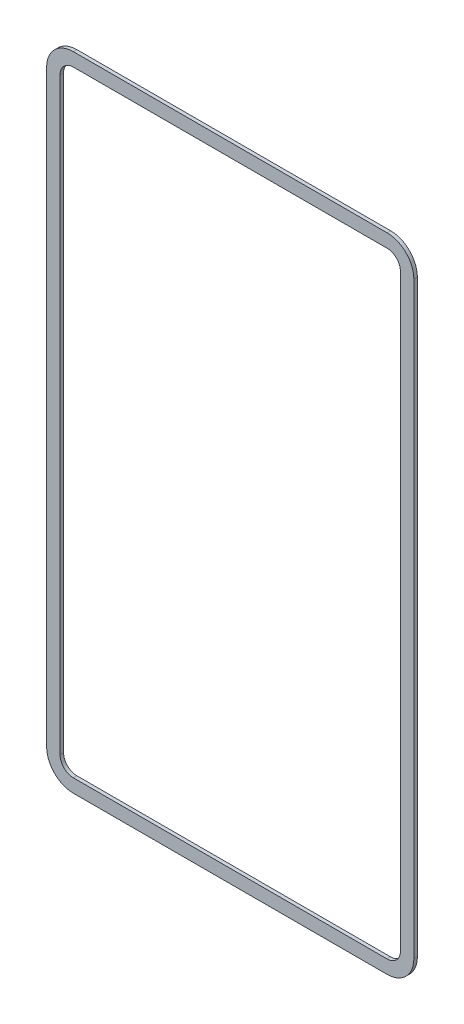
SolidWorks part; units mm, degrees
ref_plane "Front Plane" through (0, 0, 0) normal (0, 0, 1) x (1, 0, 0)
ref_plane "Top Plane" through (0, 0, 0) normal (0, 1, 0) x (1, 0, 0)
ref_plane "Right Plane" through (0, 0, 0) normal (1, 0, 0) x (0, 0, -1)
sketch "Sketch1" plane through (0, 0, 0) normal (0, 0, 1) x (1, 0, 0)
  line L0 (-103.5381, 10.9203) -> (20.9119, 10.9203) construction
  line L1 (-94.0381, 56.5203) -> (-49.4962, 56.5203)
  line L2 (-97.8381, 52.7203) -> (-97.8381, -30.8797)
  line L3 (-94.0381, -34.6797) -> (-49.4962, -34.6797)
  line L4 (-45.6962, 52.7203) -> (-45.6962, -30.8797)
  line L5 (-95.9381, 52.7203) -> (-95.9381, -30.8797)
  line L6 (-94.0381, -32.7797) -> (-49.4962, -32.7797)
  line L7 (-47.5962, 52.7203) -> (-47.5962, -30.8797)
  line L8 (-94.0381, 54.6203) -> (-49.4962, 54.6203)
  arc A0 (-97.8381, -30.8797) -> (-94.0381, -34.6797) centre (-94.0381, -30.8797) ccw
  arc A1 (-49.4962, -34.6797) -> (-45.6962, -30.8797) centre (-49.4962, -30.8797) ccw
  arc A2 (-49.4962, 56.5203) -> (-45.6962, 52.7203) centre (-49.4962, 52.7203) cw
  arc A3 (-94.0381, 56.5203) -> (-97.8381, 52.7203) centre (-94.0381, 52.7203) ccw
  arc A4 (-95.9381, -30.8797) -> (-94.0381, -32.7797) centre (-94.0381, -30.8797) ccw
  arc A5 (-49.4962, -32.7797) -> (-47.5962, -30.8797) centre (-49.4962, -30.8797) ccw
  arc A6 (-49.4962, 54.6203) -> (-47.5962, 52.7203) centre (-49.4962, 52.7203) cw
  arc A7 (-94.0381, 54.6203) -> (-95.9381, 52.7203) centre (-94.0381, 52.7203) ccw
  point P2 (-74.8638, 10.9203)
  dimension "D1" = 1.9
extrude "Boss-Extrude1" add sketch "Sketch1" along normal blind 0.5
